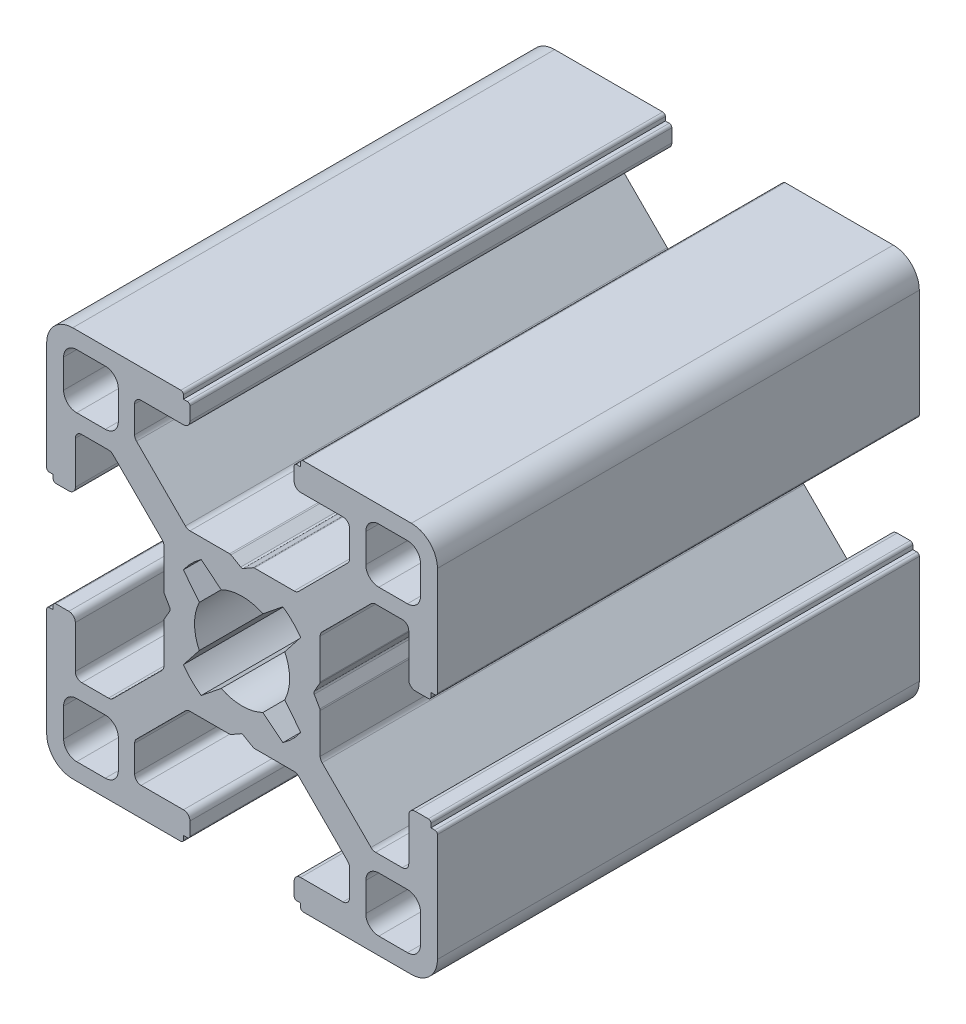
SolidWorks part; units mm, degrees
ref_plane "Alzado" through (0, 0, 0) normal (0, 0, 1) x (1, 0, 0)
ref_plane "Planta" through (0, 0, 0) normal (0, 1, 0) x (1, 0, 0)
ref_plane "Vista lateral" through (0, 0, 0) normal (1, 0, 0) x (0, 0, -1)
ref_plane "Plano1" through (0, 0, 1000) normal (0, 0, 1) x (1, 0, 0)
sketch "Croquis1" plane through (0, 0, 1000) normal (0, 0, 1) x (1, 0, 0)
  line L0 (8, -5.5) -> (5.8, -5.5)
  line L1 (4.8, -4.5) -> (4.8, -2.3)
  line L2 (5.8, -1.3) -> (8, -1.3)
  line L3 (9, -2.3) -> (9, -4.5)
  line L4 (-15.2, -5.5) -> (-17.4, -5.5)
  line L5 (-18.4, -4.5) -> (-18.4, -2.3)
  line L6 (-17.4, -1.3) -> (-15.2, -1.3)
  line L7 (-14.2, -2.3) -> (-14.2, -4.5)
  line L8 (-17.4, -24.5) -> (-15.2, -24.5)
  line L9 (-14.2, -25.5) -> (-14.2, -27.7)
  line L10 (-15.2, -28.7) -> (-17.4, -28.7)
  line L11 (-18.4, -27.7) -> (-18.4, -25.5)
  line L12 (5.8, -24.5) -> (8, -24.5)
  line L13 (9, -25.5) -> (9, -27.7)
  line L14 (8, -28.7) -> (5.8, -28.7)
  line L15 (4.8, -27.7) -> (4.8, -25.5)
  line L16 (-7.8359, -10.4816) -> (-6.3001, -11.7194)
  line L17 (-3.0999, -11.7194) -> (-1.5641, -10.4816)
  line L18 (-0.1947, -11.8453) -> (-1.4194, -13.3999)
  line L19 (-1.4194, -16.6001) -> (-0.1947, -18.1547)
  line L20 (-1.5641, -19.5184) -> (-3.0999, -18.2806)
  line L21 (-6.3001, -18.2806) -> (-7.8359, -19.5184)
  line L22 (-9.2053, -18.1547) -> (-7.9806, -16.6001)
  line L23 (-7.9806, -13.3999) -> (-9.2053, -11.8453)
  line L24 (9.8, -10.5) -> (10.1, -10.5)
  line L25 (10.3, -10.3) -> (10.3, -2)
  line L26 (8.3, 0) -> (0, 0)
  line L27 (-0.2, -0.2) -> (-0.2, -0.5)
  line L28 (-0.2, -0.5) -> (-0.5, -0.5)
  line L29 (-0.7, -0.7) -> (-0.7, -1.7)
  line L30 (-0.2, -2.2) -> (3.05, -2.2)
  line L31 (3.55, -2.7) -> (3.55, -4.7431)
  line L32 (3.4037, -5.0964) -> (-0.3491, -8.8534)
  line L33 (-0.7028, -9) -> (-3.7468, -9)
  line L34 (-3.8462, -9.0264) -> (-4.6006, -9.4583)
  line L35 (-4.7994, -9.4583) -> (-5.5538, -9.0264)
  line L36 (-5.6532, -9) -> (-8.6972, -9)
  line L37 (-9.0509, -8.8534) -> (-12.8037, -5.0964)
  line L38 (-12.95, -4.7431) -> (-12.95, -2.7)
  line L39 (-12.45, -2.2) -> (-9.2, -2.2)
  line L40 (-8.7, -1.7) -> (-8.7, -0.7)
  line L41 (-8.9, -0.5) -> (-9.2, -0.5)
  line L42 (-9.2, -0.5) -> (-9.2, -0.2)
  line L43 (-9.4, 0) -> (-17.7, 0)
  line L44 (-19.7, -2) -> (-19.7, -10.3)
  line L45 (-19.5, -10.5) -> (-19.2, -10.5)
  line L46 (-19.2, -10.5) -> (-19.2, -10.8)
  line L47 (-19, -11) -> (-18, -11)
  line L48 (-17.5, -10.5) -> (-17.5, -7.25)
  line L49 (-17, -6.75) -> (-14.9569, -6.75)
  line L50 (-14.6036, -6.8963) -> (-10.8466, -10.6491)
  line L51 (-10.7, -11.0028) -> (-10.7, -14.0468)
  line L52 (-10.6736, -14.1462) -> (-10.2417, -14.9006)
  line L53 (-10.2417, -15.0994) -> (-10.6736, -15.8538)
  line L54 (-10.7, -15.9532) -> (-10.7, -18.9972)
  line L55 (-10.8466, -19.3509) -> (-14.6036, -23.1037)
  line L56 (-14.9569, -23.25) -> (-17, -23.25)
  line L57 (-17.5, -22.75) -> (-17.5, -19.5)
  line L58 (-18, -19) -> (-19, -19)
  line L59 (-19.2, -19.2) -> (-19.2, -19.5)
  line L60 (-19.2, -19.5) -> (-19.5, -19.5)
  line L61 (-19.7, -19.7) -> (-19.7, -28)
  line L62 (-17.7, -30) -> (-9.4, -30)
  line L63 (-9.2, -29.8) -> (-9.2, -29.5)
  line L64 (-9.2, -29.5) -> (-8.9, -29.5)
  line L65 (-8.7, -29.3) -> (-8.7, -28.3)
  line L66 (-9.2, -27.8) -> (-12.45, -27.8)
  line L67 (-12.95, -27.3) -> (-12.95, -25.2569)
  line L68 (-12.8037, -24.9036) -> (-9.0509, -21.1466)
  line L69 (-8.6972, -21) -> (-5.6532, -21)
  line L70 (-5.5538, -20.9736) -> (-4.7994, -20.5417)
  line L71 (-4.6006, -20.5417) -> (-3.8462, -20.9736)
  line L72 (-3.7468, -21) -> (-0.7028, -21)
  line L73 (-0.3491, -21.1466) -> (3.4037, -24.9036)
  line L74 (3.55, -25.2569) -> (3.55, -27.3)
  line L75 (3.05, -27.8) -> (-0.2, -27.8)
  line L76 (-0.7, -28.3) -> (-0.7, -29.3)
  line L77 (-0.5, -29.5) -> (-0.2, -29.5)
  line L78 (-0.2, -29.5) -> (-0.2, -29.8)
  line L79 (0, -30) -> (8.3, -30)
  line L80 (10.3, -28) -> (10.3, -19.7)
  line L81 (10.1, -19.5) -> (9.8, -19.5)
  line L82 (9.8, -19.5) -> (9.8, -19.2)
  line L83 (9.6, -19) -> (8.6, -19)
  line L84 (8.1, -19.5) -> (8.1, -22.75)
  line L85 (7.6, -23.25) -> (5.5569, -23.25)
  line L86 (5.2036, -23.1037) -> (1.4466, -19.3509)
  line L87 (1.3, -18.9972) -> (1.3, -15.9532)
  line L88 (1.2736, -15.8538) -> (0.8417, -15.0994)
  line L89 (0.8417, -14.9006) -> (1.2736, -14.1462)
  line L90 (1.3, -14.0468) -> (1.3, -11.0028)
  line L91 (1.4466, -10.6491) -> (5.2036, -6.8963)
  line L92 (5.5569, -6.75) -> (7.6, -6.75)
  line L93 (8.1, -7.25) -> (8.1, -10.5)
  line L94 (8.6, -11) -> (9.6, -11)
  line L95 (9.8, -10.8) -> (9.8, -10.5)
  arc A0 (9, -4.5) -> (8, -5.5) centre (8, -4.5) cw
  arc A1 (5.8, -5.5) -> (4.8, -4.5) centre (5.8, -4.5) cw
  arc A2 (4.8, -2.3) -> (5.8, -1.3) centre (5.8, -2.3) cw
  arc A3 (8, -1.3) -> (9, -2.3) centre (8, -2.3) cw
  arc A4 (-14.2, -4.5) -> (-15.2, -5.5) centre (-15.2, -4.5) cw
  arc A5 (-17.4, -5.5) -> (-18.4, -4.5) centre (-17.4, -4.5) cw
  arc A6 (-18.4, -2.3) -> (-17.4, -1.3) centre (-17.4, -2.3) cw
  arc A7 (-15.2, -1.3) -> (-14.2, -2.3) centre (-15.2, -2.3) cw
  arc A8 (-18.4, -25.5) -> (-17.4, -24.5) centre (-17.4, -25.5) cw
  arc A9 (-15.2, -24.5) -> (-14.2, -25.5) centre (-15.2, -25.5) cw
  arc A10 (-14.2, -27.7) -> (-15.2, -28.7) centre (-15.2, -27.7) cw
  arc A11 (-17.4, -28.7) -> (-18.4, -27.7) centre (-17.4, -27.7) cw
  arc A12 (4.8, -25.5) -> (5.8, -24.5) centre (5.8, -25.5) cw
  arc A13 (8, -24.5) -> (9, -25.5) centre (8, -25.5) cw
  arc A14 (9, -27.7) -> (8, -28.7) centre (8, -27.7) cw
  arc A15 (5.8, -28.7) -> (4.8, -27.7) centre (5.8, -27.7) cw
  arc A16 (-9.2053, -11.8453) -> (-7.8359, -10.4816) centre (-4.7, -15) cw
  arc A17 (-6.3001, -11.7194) -> (-3.0999, -11.7194) centre (-4.7, -15) cw
  arc A18 (-1.5641, -10.4816) -> (-0.1947, -11.8453) centre (-4.7, -15) cw
  arc A19 (-1.4194, -13.3999) -> (-1.4194, -16.6001) centre (-4.7, -15) cw
  arc A20 (-0.1947, -18.1547) -> (-1.5641, -19.5184) centre (-4.7, -15) cw
  arc A21 (-3.0999, -18.2806) -> (-6.3001, -18.2806) centre (-4.7, -15) cw
  arc A22 (-7.8359, -19.5184) -> (-9.2053, -18.1547) centre (-4.7, -15) cw
  arc A23 (-7.9806, -16.6001) -> (-7.9806, -13.3999) centre (-4.7, -15) cw
  arc A24 (10.1, -10.5) -> (10.3, -10.3) centre (10.1, -10.3) ccw
  arc A25 (10.3, -2) -> (8.3, 0) centre (8.3, -2) ccw
  arc A26 (0, 0) -> (-0.2, -0.2) centre (0, -0.2) ccw
  arc A27 (-0.5, -0.5) -> (-0.7, -0.7) centre (-0.5, -0.7) ccw
  arc A28 (-0.7, -1.7) -> (-0.2, -2.2) centre (-0.2, -1.7) ccw
  arc A29 (3.05, -2.2) -> (3.55, -2.7) centre (3.05, -2.7) cw
  arc A30 (3.55, -4.7431) -> (3.4037, -5.0964) centre (3.05, -4.7431) cw
  arc A31 (-0.3491, -8.8534) -> (-0.7028, -9) centre (-0.7028, -8.5) cw
  arc A32 (-3.7468, -9) -> (-3.8462, -9.0264) centre (-3.7468, -9.2) ccw
  arc A33 (-4.6006, -9.4583) -> (-4.7994, -9.4583) centre (-4.7, -9.2847) cw
  arc A34 (-5.5538, -9.0264) -> (-5.6532, -9) centre (-5.6532, -9.2) ccw
  arc A35 (-8.6972, -9) -> (-9.0509, -8.8534) centre (-8.6972, -8.5) cw
  arc A36 (-12.8037, -5.0964) -> (-12.95, -4.7431) centre (-12.45, -4.7431) cw
  arc A37 (-12.95, -2.7) -> (-12.45, -2.2) centre (-12.45, -2.7) cw
  arc A38 (-9.2, -2.2) -> (-8.7, -1.7) centre (-9.2, -1.7) ccw
  arc A39 (-8.7, -0.7) -> (-8.9, -0.5) centre (-8.9, -0.7) ccw
  arc A40 (-9.2, -0.2) -> (-9.4, 0) centre (-9.4, -0.2) ccw
  arc A41 (-17.7, 0) -> (-19.7, -2) centre (-17.7, -2) ccw
  arc A42 (-19.7, -10.3) -> (-19.5, -10.5) centre (-19.5, -10.3) ccw
  arc A43 (-19.2, -10.8) -> (-19, -11) centre (-19, -10.8) ccw
  arc A44 (-18, -11) -> (-17.5, -10.5) centre (-18, -10.5) ccw
  arc A45 (-17.5, -7.25) -> (-17, -6.75) centre (-17, -7.25) cw
  arc A46 (-14.9569, -6.75) -> (-14.6036, -6.8963) centre (-14.9569, -7.25) cw
  arc A47 (-10.8466, -10.6491) -> (-10.7, -11.0028) centre (-11.2, -11.0028) cw
  arc A48 (-10.7, -14.0468) -> (-10.6736, -14.1462) centre (-10.5, -14.0468) ccw
  arc A49 (-10.2417, -14.9006) -> (-10.2417, -15.0994) centre (-10.4153, -15) cw
  arc A50 (-10.6736, -15.8538) -> (-10.7, -15.9532) centre (-10.5, -15.9532) ccw
  arc A51 (-10.7, -18.9972) -> (-10.8466, -19.3509) centre (-11.2, -18.9972) cw
  arc A52 (-14.6036, -23.1037) -> (-14.9569, -23.25) centre (-14.9569, -22.75) cw
  arc A53 (-17, -23.25) -> (-17.5, -22.75) centre (-17, -22.75) cw
  arc A54 (-17.5, -19.5) -> (-18, -19) centre (-18, -19.5) ccw
  arc A55 (-19, -19) -> (-19.2, -19.2) centre (-19, -19.2) ccw
  arc A56 (-19.5, -19.5) -> (-19.7, -19.7) centre (-19.5, -19.7) ccw
  arc A57 (-19.7, -28) -> (-17.7, -30) centre (-17.7, -28) ccw
  arc A58 (-9.4, -30) -> (-9.2, -29.8) centre (-9.4, -29.8) ccw
  arc A59 (-8.9, -29.5) -> (-8.7, -29.3) centre (-8.9, -29.3) ccw
  arc A60 (-8.7, -28.3) -> (-9.2, -27.8) centre (-9.2, -28.3) ccw
  arc A61 (-12.45, -27.8) -> (-12.95, -27.3) centre (-12.45, -27.3) cw
  arc A62 (-12.95, -25.2569) -> (-12.8037, -24.9036) centre (-12.45, -25.2569) cw
  arc A63 (-9.0509, -21.1466) -> (-8.6972, -21) centre (-8.6972, -21.5) cw
  arc A64 (-5.6532, -21) -> (-5.5538, -20.9736) centre (-5.6532, -20.8) ccw
  arc A65 (-4.7994, -20.5417) -> (-4.6006, -20.5417) centre (-4.7, -20.7153) cw
  arc A66 (-3.8462, -20.9736) -> (-3.7468, -21) centre (-3.7468, -20.8) ccw
  arc A67 (-0.7028, -21) -> (-0.3491, -21.1466) centre (-0.7028, -21.5) cw
  arc A68 (3.4037, -24.9036) -> (3.55, -25.2569) centre (3.05, -25.2569) cw
  arc A69 (3.55, -27.3) -> (3.05, -27.8) centre (3.05, -27.3) cw
  arc A70 (-0.2, -27.8) -> (-0.7, -28.3) centre (-0.2, -28.3) ccw
  arc A71 (-0.7, -29.3) -> (-0.5, -29.5) centre (-0.5, -29.3) ccw
  arc A72 (-0.2, -29.8) -> (0, -30) centre (0, -29.8) ccw
  arc A73 (8.3, -30) -> (10.3, -28) centre (8.3, -28) ccw
  arc A74 (10.3, -19.7) -> (10.1, -19.5) centre (10.1, -19.7) ccw
  arc A75 (9.8, -19.2) -> (9.6, -19) centre (9.6, -19.2) ccw
  arc A76 (8.6, -19) -> (8.1, -19.5) centre (8.6, -19.5) ccw
  arc A77 (8.1, -22.75) -> (7.6, -23.25) centre (7.6, -22.75) cw
  arc A78 (5.5569, -23.25) -> (5.2036, -23.1037) centre (5.5569, -22.75) cw
  arc A79 (1.4466, -19.3509) -> (1.3, -18.9972) centre (1.8, -18.9972) cw
  arc A80 (1.3, -15.9532) -> (1.2736, -15.8538) centre (1.1, -15.9532) ccw
  arc A81 (0.8417, -15.0994) -> (0.8417, -14.9006) centre (1.0153, -15) cw
  arc A82 (1.2736, -14.1462) -> (1.3, -14.0468) centre (1.1, -14.0468) ccw
  arc A83 (1.3, -11.0028) -> (1.4466, -10.6491) centre (1.8, -11.0028) cw
  arc A84 (5.2036, -6.8963) -> (5.5569, -6.75) centre (5.5569, -7.25) cw
  arc A85 (7.6, -6.75) -> (8.1, -7.25) centre (7.6, -7.25) cw
  arc A86 (8.1, -10.5) -> (8.6, -11) centre (8.6, -10.5) ccw
  arc A87 (9.6, -11) -> (9.8, -10.8) centre (9.6, -10.8) ccw
extrude "Saliente-Extruir1" add sketch "Croquis1" against normal blind 1000
sketch "Croquis4" plane through (0, 0, 0) normal (0, 0, -1) x (-1, 0, 0)
  line L72 (-9.8, -10.5) -> (-9.8, -10.8)
  line L73 (-9.6, -11) -> (-8.6, -11)
  line L74 (-8.1, -10.5) -> (-8.1, -7.25)
  line L75 (-7.6, -6.75) -> (-5.5569, -6.75)
  line L76 (-5.2036, -6.8963) -> (-1.4466, -10.6491)
  line L77 (-1.3, -11.0028) -> (-1.3, -14.0468)
  line L78 (-1.2736, -14.1462) -> (-0.8417, -14.9006)
  line L79 (-0.8417, -15.0994) -> (-1.2736, -15.8538)
  line L80 (-1.3, -15.9532) -> (-1.3, -18.9972)
  line L81 (-1.4466, -19.3509) -> (-5.2036, -23.1037)
  line L82 (-5.5569, -23.25) -> (-7.6, -23.25)
  line L83 (-8.1, -22.75) -> (-8.1, -19.5)
  line L84 (-8.6, -19) -> (-9.6, -19)
  line L85 (-9.8, -19.2) -> (-9.8, -19.5)
  line L86 (-9.8, -19.5) -> (-10.1, -19.5)
  line L87 (-10.3, -19.7) -> (-10.3, -28)
  line L88 (-8.3, -30) -> (0, -30)
  line L89 (0.2, -29.8) -> (0.2, -29.5)
  line L90 (0.2, -29.5) -> (0.5, -29.5)
  line L91 (0.7, -29.3) -> (0.7, -28.3)
  line L92 (0.2, -27.8) -> (-3.05, -27.8)
  line L93 (-3.55, -27.3) -> (-3.55, -25.2569)
  line L94 (-3.4037, -24.9036) -> (0.3491, -21.1466)
  line L95 (0.7028, -21) -> (3.7468, -21)
  line L96 (3.8462, -20.9736) -> (4.6006, -20.5417)
  line L97 (4.7994, -20.5417) -> (5.5538, -20.9736)
  line L98 (5.6532, -21) -> (8.6972, -21)
  line L99 (9.0509, -21.1466) -> (12.8037, -24.9036)
  line L100 (12.95, -25.2569) -> (12.95, -27.3)
  line L101 (12.45, -27.8) -> (9.2, -27.8)
  line L102 (8.7, -28.3) -> (8.7, -29.3)
  line L103 (8.9, -29.5) -> (9.2, -29.5)
  line L104 (9.2, -29.5) -> (9.2, -29.8)
  line L105 (9.4, -30) -> (17.7, -30)
  line L106 (19.7, -28) -> (19.7, -19.7)
  line L107 (19.5, -19.5) -> (19.2, -19.5)
  line L108 (19.2, -19.5) -> (19.2, -19.2)
  line L109 (19, -19) -> (18, -19)
  line L110 (17.5, -19.5) -> (17.5, -22.75)
  line L111 (17, -23.25) -> (14.9569, -23.25)
  line L112 (14.6036, -23.1037) -> (10.8466, -19.3509)
  line L113 (10.7, -18.9972) -> (10.7, -15.9532)
  line L114 (10.6736, -15.8538) -> (10.2417, -15.0994)
  line L115 (10.2417, -14.9006) -> (10.6736, -14.1462)
  line L116 (10.7, -14.0468) -> (10.7, -11.0028)
  line L117 (10.8466, -10.6491) -> (14.6036, -6.8963)
  line L118 (14.9569, -6.75) -> (17, -6.75)
  line L119 (17.5, -7.25) -> (17.5, -10.5)
  line L120 (18, -11) -> (19, -11)
  line L121 (19.2, -10.8) -> (19.2, -10.5)
  line L122 (19.2, -10.5) -> (19.5, -10.5)
  line L123 (19.7, -10.3) -> (19.7, -2)
  line L124 (17.7, 0) -> (9.4, 0)
  line L125 (9.2, -0.2) -> (9.2, -0.5)
  line L126 (9.2, -0.5) -> (8.9, -0.5)
  line L127 (8.7, -0.7) -> (8.7, -1.7)
  line L128 (9.2, -2.2) -> (12.45, -2.2)
  line L129 (12.95, -2.7) -> (12.95, -4.7431)
  line L130 (12.8037, -5.0964) -> (9.0509, -8.8534)
  line L131 (8.6972, -9) -> (5.6532, -9)
  line L132 (5.5538, -9.0264) -> (4.7994, -9.4583)
  line L133 (4.6006, -9.4583) -> (3.8462, -9.0264)
  line L134 (3.7468, -9) -> (0.7028, -9)
  line L135 (0.3491, -8.8534) -> (-3.4037, -5.0964)
  line L136 (-3.55, -4.7431) -> (-3.55, -2.7)
  line L137 (-3.05, -2.2) -> (0.2, -2.2)
  line L138 (0.7, -1.7) -> (0.7, -0.7)
  line L139 (0.5, -0.5) -> (0.2, -0.5)
  line L140 (0.2, -0.5) -> (0.2, -0.2)
  line L141 (0, 0) -> (-8.3, 0)
  line L142 (-10.3, -2) -> (-10.3, -10.3)
  line L143 (-10.1, -10.5) -> (-9.8, -10.5)
  line L144 (-9.8, -10.5) -> (-9.8, -10.8)
  line L145 (-9.6, -11) -> (-8.6, -11)
  line L146 (-8.1, -10.5) -> (-8.1, -7.25)
  line L147 (-7.6, -6.75) -> (-5.5569, -6.75)
  line L148 (-5.2036, -6.8963) -> (-1.4466, -10.6491)
  line L149 (-1.3, -11.0028) -> (-1.3, -14.0468)
  line L150 (-1.2736, -14.1462) -> (-0.8417, -14.9006)
  line L151 (-0.8417, -15.0994) -> (-1.2736, -15.8538)
  line L152 (-1.3, -15.9532) -> (-1.3, -18.9972)
  line L153 (-1.4466, -19.3509) -> (-5.2036, -23.1037)
  line L154 (-5.5569, -23.25) -> (-7.6, -23.25)
  line L155 (-8.1, -22.75) -> (-8.1, -19.5)
  line L156 (-8.6, -19) -> (-9.6, -19)
  line L157 (-9.8, -19.2) -> (-9.8, -19.5)
  line L158 (-9.8, -19.5) -> (-10.1, -19.5)
  line L159 (-10.3, -19.7) -> (-10.3, -28)
  line L160 (-8.3, -30) -> (0, -30)
  line L161 (0.2, -29.8) -> (0.2, -29.5)
  line L162 (0.2, -29.5) -> (0.5, -29.5)
  line L163 (0.7, -29.3) -> (0.7, -28.3)
  line L164 (0.2, -27.8) -> (-3.05, -27.8)
  line L165 (-3.55, -27.3) -> (-3.55, -25.2569)
  line L166 (-3.4037, -24.9036) -> (0.3491, -21.1466)
  line L167 (0.7028, -21) -> (3.7468, -21)
  line L168 (3.8462, -20.9736) -> (4.6006, -20.5417)
  line L169 (4.7994, -20.5417) -> (5.5538, -20.9736)
  line L170 (5.6532, -21) -> (8.6972, -21)
  line L171 (9.0509, -21.1466) -> (12.8037, -24.9036)
  line L172 (12.95, -25.2569) -> (12.95, -27.3)
  line L173 (12.45, -27.8) -> (9.2, -27.8)
  line L174 (8.7, -28.3) -> (8.7, -29.3)
  line L175 (8.9, -29.5) -> (9.2, -29.5)
  line L176 (9.2, -29.5) -> (9.2, -29.8)
  line L177 (9.4, -30) -> (17.7, -30)
  line L178 (19.7, -28) -> (19.7, -19.7)
  line L179 (19.5, -19.5) -> (19.2, -19.5)
  line L180 (19.2, -19.5) -> (19.2, -19.2)
  line L181 (19, -19) -> (18, -19)
  line L182 (17.5, -19.5) -> (17.5, -22.75)
  line L183 (17, -23.25) -> (14.9569, -23.25)
  line L184 (14.6036, -23.1037) -> (10.8466, -19.3509)
  line L185 (10.7, -18.9972) -> (10.7, -15.9532)
  line L186 (10.6736, -15.8538) -> (10.2417, -15.0994)
  line L187 (10.2417, -14.9006) -> (10.6736, -14.1462)
  line L188 (10.7, -14.0468) -> (10.7, -11.0028)
  line L189 (10.8466, -10.6491) -> (14.6036, -6.8963)
  line L190 (14.9569, -6.75) -> (17, -6.75)
  line L191 (17.5, -7.25) -> (17.5, -10.5)
  line L192 (18, -11) -> (19, -11)
  line L193 (19.2, -10.8) -> (19.2, -10.5)
  line L194 (19.2, -10.5) -> (19.5, -10.5)
  line L195 (19.7, -10.3) -> (19.7, -2)
  line L196 (17.7, 0) -> (9.4, 0)
  line L197 (9.2, -0.2) -> (9.2, -0.5)
  line L198 (9.2, -0.5) -> (8.9, -0.5)
  line L199 (8.7, -0.7) -> (8.7, -1.7)
  line L200 (9.2, -2.2) -> (12.45, -2.2)
  line L201 (12.95, -2.7) -> (12.95, -4.7431)
  line L202 (12.8037, -5.0964) -> (9.0509, -8.8534)
  line L203 (8.6972, -9) -> (5.6532, -9)
  line L204 (5.5538, -9.0264) -> (4.7994, -9.4583)
  line L205 (4.6006, -9.4583) -> (3.8462, -9.0264)
  line L206 (3.7468, -9) -> (0.7028, -9)
  line L207 (0.3491, -8.8534) -> (-3.4037, -5.0964)
  line L208 (-3.55, -4.7431) -> (-3.55, -2.7)
  line L209 (-3.05, -2.2) -> (0.2, -2.2)
  line L210 (0.7, -1.7) -> (0.7, -0.7)
  line L211 (0.5, -0.5) -> (0.2, -0.5)
  line L212 (0.2, -0.5) -> (0.2, -0.2)
  line L213 (0, 0) -> (-8.3, 0)
  line L214 (-10.3, -2) -> (-10.3, -10.3)
  line L215 (-10.1, -10.5) -> (-9.8, -10.5)
  arc A64 (-9.8, -10.8) -> (-9.6, -11) centre (-9.6, -10.8) ccw
  arc A65 (-8.6, -11) -> (-8.1, -10.5) centre (-8.6, -10.5) ccw
  arc A66 (-7.6, -6.75) -> (-8.1, -7.25) centre (-7.6, -7.25) ccw
  arc A67 (-5.2036, -6.8963) -> (-5.5569, -6.75) centre (-5.5569, -7.25) ccw
  arc A68 (-1.3, -11.0028) -> (-1.4466, -10.6491) centre (-1.8, -11.0028) ccw
  arc A69 (-1.3, -14.0468) -> (-1.2736, -14.1462) centre (-1.1, -14.0468) ccw
  arc A70 (-0.8417, -15.0994) -> (-0.8417, -14.9006) centre (-1.0153, -15) ccw
  arc A71 (-1.2736, -15.8538) -> (-1.3, -15.9532) centre (-1.1, -15.9532) ccw
  arc A72 (-1.4466, -19.3509) -> (-1.3, -18.9972) centre (-1.8, -18.9972) ccw
  arc A73 (-5.5569, -23.25) -> (-5.2036, -23.1037) centre (-5.5569, -22.75) ccw
  arc A74 (-8.1, -22.75) -> (-7.6, -23.25) centre (-7.6, -22.75) ccw
  arc A75 (-8.1, -19.5) -> (-8.6, -19) centre (-8.6, -19.5) ccw
  arc A76 (-9.6, -19) -> (-9.8, -19.2) centre (-9.6, -19.2) ccw
  arc A77 (-10.1, -19.5) -> (-10.3, -19.7) centre (-10.1, -19.7) ccw
  arc A78 (-10.3, -28) -> (-8.3, -30) centre (-8.3, -28) ccw
  arc A79 (0, -30) -> (0.2, -29.8) centre (0, -29.8) ccw
  arc A80 (0.5, -29.5) -> (0.7, -29.3) centre (0.5, -29.3) ccw
  arc A81 (0.7, -28.3) -> (0.2, -27.8) centre (0.2, -28.3) ccw
  arc A82 (-3.55, -27.3) -> (-3.05, -27.8) centre (-3.05, -27.3) ccw
  arc A83 (-3.4037, -24.9036) -> (-3.55, -25.2569) centre (-3.05, -25.2569) ccw
  arc A84 (0.7028, -21) -> (0.3491, -21.1466) centre (0.7028, -21.5) ccw
  arc A85 (3.7468, -21) -> (3.8462, -20.9736) centre (3.7468, -20.8) ccw
  arc A86 (4.7994, -20.5417) -> (4.6006, -20.5417) centre (4.7, -20.7153) ccw
  arc A87 (5.5538, -20.9736) -> (5.6532, -21) centre (5.6532, -20.8) ccw
  arc A88 (9.0509, -21.1466) -> (8.6972, -21) centre (8.6972, -21.5) ccw
  arc A89 (12.95, -25.2569) -> (12.8037, -24.9036) centre (12.45, -25.2569) ccw
  arc A90 (12.45, -27.8) -> (12.95, -27.3) centre (12.45, -27.3) ccw
  arc A91 (9.2, -27.8) -> (8.7, -28.3) centre (9.2, -28.3) ccw
  arc A92 (8.7, -29.3) -> (8.9, -29.5) centre (8.9, -29.3) ccw
  arc A93 (9.2, -29.8) -> (9.4, -30) centre (9.4, -29.8) ccw
  arc A94 (17.7, -30) -> (19.7, -28) centre (17.7, -28) ccw
  arc A95 (19.7, -19.7) -> (19.5, -19.5) centre (19.5, -19.7) ccw
  arc A96 (19.2, -19.2) -> (19, -19) centre (19, -19.2) ccw
  arc A97 (18, -19) -> (17.5, -19.5) centre (18, -19.5) ccw
  arc A98 (17, -23.25) -> (17.5, -22.75) centre (17, -22.75) ccw
  arc A99 (14.6036, -23.1037) -> (14.9569, -23.25) centre (14.9569, -22.75) ccw
  arc A100 (10.7, -18.9972) -> (10.8466, -19.3509) centre (11.2, -18.9972) ccw
  arc A101 (10.7, -15.9532) -> (10.6736, -15.8538) centre (10.5, -15.9532) ccw
  arc A102 (10.2417, -14.9006) -> (10.2417, -15.0994) centre (10.4153, -15) ccw
  arc A103 (10.6736, -14.1462) -> (10.7, -14.0468) centre (10.5, -14.0468) ccw
  arc A104 (10.8466, -10.6491) -> (10.7, -11.0028) centre (11.2, -11.0028) ccw
  arc A105 (14.9569, -6.75) -> (14.6036, -6.8963) centre (14.9569, -7.25) ccw
  arc A106 (17.5, -7.25) -> (17, -6.75) centre (17, -7.25) ccw
  arc A107 (17.5, -10.5) -> (18, -11) centre (18, -10.5) ccw
  arc A108 (19, -11) -> (19.2, -10.8) centre (19, -10.8) ccw
  arc A109 (19.5, -10.5) -> (19.7, -10.3) centre (19.5, -10.3) ccw
  arc A110 (19.7, -2) -> (17.7, 0) centre (17.7, -2) ccw
  arc A111 (9.4, 0) -> (9.2, -0.2) centre (9.4, -0.2) ccw
  arc A112 (8.9, -0.5) -> (8.7, -0.7) centre (8.9, -0.7) ccw
  arc A113 (8.7, -1.7) -> (9.2, -2.2) centre (9.2, -1.7) ccw
  arc A114 (12.95, -2.7) -> (12.45, -2.2) centre (12.45, -2.7) ccw
  arc A115 (12.8037, -5.0964) -> (12.95, -4.7431) centre (12.45, -4.7431) ccw
  arc A116 (8.6972, -9) -> (9.0509, -8.8534) centre (8.6972, -8.5) ccw
  arc A117 (5.6532, -9) -> (5.5538, -9.0264) centre (5.6532, -9.2) ccw
  arc A118 (4.6006, -9.4583) -> (4.7994, -9.4583) centre (4.7, -9.2847) ccw
  arc A119 (3.8462, -9.0264) -> (3.7468, -9) centre (3.7468, -9.2) ccw
  arc A120 (0.3491, -8.8534) -> (0.7028, -9) centre (0.7028, -8.5) ccw
  arc A121 (-3.55, -4.7431) -> (-3.4037, -5.0964) centre (-3.05, -4.7431) ccw
  arc A122 (-3.05, -2.2) -> (-3.55, -2.7) centre (-3.05, -2.7) ccw
  arc A123 (0.2, -2.2) -> (0.7, -1.7) centre (0.2, -1.7) ccw
  arc A124 (0.7, -0.7) -> (0.5, -0.5) centre (0.5, -0.7) ccw
  arc A125 (0.2, -0.2) -> (0, 0) centre (0, -0.2) ccw
  arc A126 (-8.3, 0) -> (-10.3, -2) centre (-8.3, -2) ccw
  arc A127 (-10.3, -10.3) -> (-10.1, -10.5) centre (-10.1, -10.3) ccw
  arc A128 (-9.8, -10.8) -> (-9.6, -11) centre (-9.6, -10.8) ccw
  arc A129 (-8.6, -11) -> (-8.1, -10.5) centre (-8.6, -10.5) ccw
  arc A130 (-7.6, -6.75) -> (-8.1, -7.25) centre (-7.6, -7.25) ccw
  arc A131 (-5.2036, -6.8963) -> (-5.5569, -6.75) centre (-5.5569, -7.25) ccw
  arc A132 (-1.3, -11.0028) -> (-1.4466, -10.6491) centre (-1.8, -11.0028) ccw
  arc A133 (-1.3, -14.0468) -> (-1.2736, -14.1462) centre (-1.1, -14.0468) ccw
  arc A134 (-0.8417, -15.0994) -> (-0.8417, -14.9006) centre (-1.0153, -15) ccw
  arc A135 (-1.2736, -15.8538) -> (-1.3, -15.9532) centre (-1.1, -15.9532) ccw
  arc A136 (-1.4466, -19.3509) -> (-1.3, -18.9972) centre (-1.8, -18.9972) ccw
  arc A137 (-5.5569, -23.25) -> (-5.2036, -23.1037) centre (-5.5569, -22.75) ccw
  arc A138 (-8.1, -22.75) -> (-7.6, -23.25) centre (-7.6, -22.75) ccw
  arc A139 (-8.1, -19.5) -> (-8.6, -19) centre (-8.6, -19.5) ccw
  arc A140 (-9.6, -19) -> (-9.8, -19.2) centre (-9.6, -19.2) ccw
  arc A141 (-10.1, -19.5) -> (-10.3, -19.7) centre (-10.1, -19.7) ccw
  arc A142 (-10.3, -28) -> (-8.3, -30) centre (-8.3, -28) ccw
  arc A143 (0, -30) -> (0.2, -29.8) centre (0, -29.8) ccw
  arc A144 (0.5, -29.5) -> (0.7, -29.3) centre (0.5, -29.3) ccw
  arc A145 (0.7, -28.3) -> (0.2, -27.8) centre (0.2, -28.3) ccw
  arc A146 (-3.55, -27.3) -> (-3.05, -27.8) centre (-3.05, -27.3) ccw
  arc A147 (-3.4037, -24.9036) -> (-3.55, -25.2569) centre (-3.05, -25.2569) ccw
  arc A148 (0.7028, -21) -> (0.3491, -21.1466) centre (0.7028, -21.5) ccw
  arc A149 (3.7468, -21) -> (3.8462, -20.9736) centre (3.7468, -20.8) ccw
  arc A150 (4.7994, -20.5417) -> (4.6006, -20.5417) centre (4.7, -20.7153) ccw
  arc A151 (5.5538, -20.9736) -> (5.6532, -21) centre (5.6532, -20.8) ccw
  arc A152 (9.0509, -21.1466) -> (8.6972, -21) centre (8.6972, -21.5) ccw
  arc A153 (12.95, -25.2569) -> (12.8037, -24.9036) centre (12.45, -25.2569) ccw
  arc A154 (12.45, -27.8) -> (12.95, -27.3) centre (12.45, -27.3) ccw
  arc A155 (9.2, -27.8) -> (8.7, -28.3) centre (9.2, -28.3) ccw
  arc A156 (8.7, -29.3) -> (8.9, -29.5) centre (8.9, -29.3) ccw
  arc A157 (9.2, -29.8) -> (9.4, -30) centre (9.4, -29.8) ccw
  arc A158 (17.7, -30) -> (19.7, -28) centre (17.7, -28) ccw
  arc A159 (19.7, -19.7) -> (19.5, -19.5) centre (19.5, -19.7) ccw
  arc A160 (19.2, -19.2) -> (19, -19) centre (19, -19.2) ccw
  arc A161 (18, -19) -> (17.5, -19.5) centre (18, -19.5) ccw
  arc A162 (17, -23.25) -> (17.5, -22.75) centre (17, -22.75) ccw
  arc A163 (14.6036, -23.1037) -> (14.9569, -23.25) centre (14.9569, -22.75) ccw
  arc A164 (10.7, -18.9972) -> (10.8466, -19.3509) centre (11.2, -18.9972) ccw
  arc A165 (10.7, -15.9532) -> (10.6736, -15.8538) centre (10.5, -15.9532) ccw
  arc A166 (10.2417, -14.9006) -> (10.2417, -15.0994) centre (10.4153, -15) ccw
  arc A167 (10.6736, -14.1462) -> (10.7, -14.0468) centre (10.5, -14.0468) ccw
  arc A168 (10.8466, -10.6491) -> (10.7, -11.0028) centre (11.2, -11.0028) ccw
  arc A169 (14.9569, -6.75) -> (14.6036, -6.8963) centre (14.9569, -7.25) ccw
  arc A170 (17.5, -7.25) -> (17, -6.75) centre (17, -7.25) ccw
  arc A171 (17.5, -10.5) -> (18, -11) centre (18, -10.5) ccw
  arc A172 (19, -11) -> (19.2, -10.8) centre (19, -10.8) ccw
  arc A173 (19.5, -10.5) -> (19.7, -10.3) centre (19.5, -10.3) ccw
  arc A174 (19.7, -2) -> (17.7, 0) centre (17.7, -2) ccw
  arc A175 (9.4, 0) -> (9.2, -0.2) centre (9.4, -0.2) ccw
  arc A176 (8.9, -0.5) -> (8.7, -0.7) centre (8.9, -0.7) ccw
  arc A177 (8.7, -1.7) -> (9.2, -2.2) centre (9.2, -1.7) ccw
  arc A178 (12.95, -2.7) -> (12.45, -2.2) centre (12.45, -2.7) ccw
  arc A179 (12.8037, -5.0964) -> (12.95, -4.7431) centre (12.45, -4.7431) ccw
  arc A180 (8.6972, -9) -> (9.0509, -8.8534) centre (8.6972, -8.5) ccw
  arc A181 (5.6532, -9) -> (5.5538, -9.0264) centre (5.6532, -9.2) ccw
  arc A182 (4.6006, -9.4583) -> (4.7994, -9.4583) centre (4.7, -9.2847) ccw
  arc A183 (3.8462, -9.0264) -> (3.7468, -9) centre (3.7468, -9.2) ccw
  arc A184 (0.3491, -8.8534) -> (0.7028, -9) centre (0.7028, -8.5) ccw
  arc A185 (-3.55, -4.7431) -> (-3.4037, -5.0964) centre (-3.05, -4.7431) ccw
  arc A186 (-3.05, -2.2) -> (-3.55, -2.7) centre (-3.05, -2.7) ccw
  arc A187 (0.2, -2.2) -> (0.7, -1.7) centre (0.2, -1.7) ccw
  arc A188 (0.7, -0.7) -> (0.5, -0.5) centre (0.5, -0.7) ccw
  arc A189 (0.2, -0.2) -> (0, 0) centre (0, -0.2) ccw
  arc A190 (-8.3, 0) -> (-10.3, -2) centre (-8.3, -2) ccw
  arc A191 (-10.3, -10.3) -> (-10.1, -10.5) centre (-10.1, -10.3) ccw
  dimension "D1" = 0
extrude "Cortar-Extruir1" cut sketch "Croquis4" against normal blind 963
